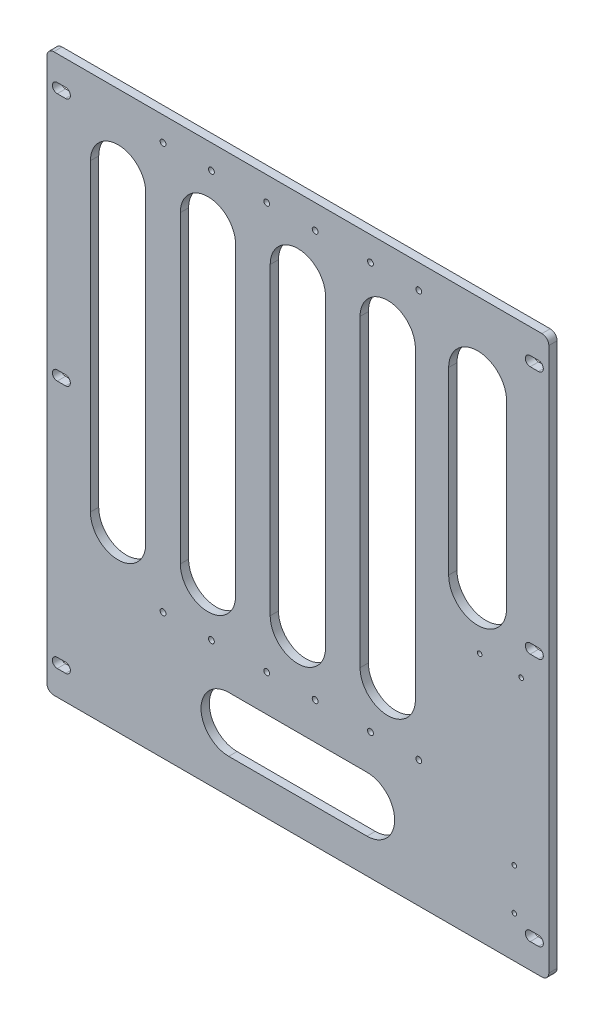
SolidWorks part; units mm, degrees
material "A-玻璃纤维"
ref_plane "前视基准面" through (0, 0, 0) normal (0, 0, 1) x (1, 0, 0)
ref_plane "上视基准面" through (0, 0, 0) normal (0, 1, 0) x (1, 0, 0)
ref_plane "右视基准面" through (0, 0, 0) normal (1, 0, 0) x (0, 0, -1)
sketch "草图1" plane through (0, 0, 0) normal (0, 0, 1) x (1, 0, 0)
  line L1 (-181.5, 201.5) -> (181.5, 201.5)
  line L2 (-181.5, 201.5) -> (-181.5, -201.5)
  line L3 (-181.5, -201.5) -> (181.5, -201.5)
  line L4 (181.5, 201.5) -> (181.5, -201.5)
  line L5 (-181.5, 201.5) -> (181.5, -201.5) construction
  line L6 (-181.5, -201.5) -> (181.5, 201.5) construction
  point P0 (0, 0)
  dimension "D1" = 363
  dimension "D2" = 403
extrude "凸台-拉伸1" add sketch "草图1" along normal blind 6
fillet "圆角1" radius 5 4 edges at (-181.5, 201.5, 3) (181.5, 201.5, 3) (181.5, -201.5, 3) (-181.5, -201.5, 3)
sketch "草图3" plane through (0, 0, 6) normal (0, 0, 1) x (1, 0, 0)
  line L0 (0, 0) -> (-324.6657, 0) construction
  line L2 (0, 0) -> (0, 277.8571) construction
  line L4 (-181.5, 196.5) -> (-181.5, -196.5) construction
  circle A0 centre (-171, -180) radius 3.5
  circle A1 centre (-171, 180) radius 3.5
  circle A3 centre (-171, 0) radius 3.5
  circle A4 centre (171, 0) radius 3.5
  circle A5 centre (171, 180) radius 3.5
  circle A6 centre (171, -180) radius 3.5
  point P0 (-171, -180)
  dimension "D4" = 7
  dimension "D3" = 7
  dimension "D6" = 7
  dimension "D1" = 10.5
  dimension "D2" = 180
  dimension "D8" = 180
extrude "切除-拉伸2" cut sketch "草图3" against normal blind 10
hole_wizard "M5 螺纹孔1" positions "草图4" profile "草图5" tap size "M5" standard "GB"
sketch "草图4" plane through (0, 0, 6) normal (0, 0, 1) x (1, 0, 0)
  line L0 (0, 0) -> (-232.1316, 0) construction
  line L2 (-181.5, 196.5) -> (-181.5, -196.5) construction
  line L4 (0, 0) -> (0, 259.9529) construction
  point P0 (-97.5, -110)
  point P2 (-62.5, -110)
  point P40 (-97.5, 184)
  point P42 (-62.5, 184)
  point P52 (-22.5, -110)
  point P53 (12.5, -110)
  point P54 (-22.5, 184)
  point P55 (12.5, 184)
  point P56 (52.5, -110)
  point P57 (87.5, -110)
  point P58 (52.5, 184)
  point P59 (87.5, 184)
  point P72 (162.5, 184) [skipped]
  point P73 (127.5, 184) [skipped]
  point P74 (162.5, -110) [skipped]
  point P75 (127.5, -110) [skipped]
  dimension "D1" = 110
  dimension "D2" = 4
  dimension "D3" = 84
  dimension "D4" = 35
  dimension "D5" = 84
  dimension "D6" = 35
  dimension "D7" = 294
sketch "草图5" plane through (-97.5, -110, 6) normal (1, 0, 0) x (0, -1, 0)
  line L0 (0, 0) -> (0, 13.6618)
  line L1 (0, 13.6618) -> (2.1, 12.4)
  line L2 (2.1, 12.4) -> (2.1, 0)
  line L5 (2.1, 0) -> (0, 0)
  line L10 (0, 13.6618) -> (-2.1, 12.4) construction
  line L11 (0, -6.35) -> (0, 107.95) construction
  dimension "螺纹孔钻头直径" = 4.2
  dimension "螺纹孔钻头深度" = 12.4
  dimension "导头角度" = 118
cosmetic thread "孔螺蚊线3" parameters "D1"=6, "D2"=5
cosmetic thread "孔螺蚊线4" parameters "D1"=6, "D2"=5
cosmetic thread "孔螺蚊线7" parameters "D1"=6, "D2"=5
cosmetic thread "孔螺蚊线8" parameters "D1"=6, "D2"=5
cosmetic thread "孔螺蚊线9" parameters "D1"=6, "D2"=5
cosmetic thread "孔螺蚊线10" parameters "D1"=6, "D2"=5
cosmetic thread "孔螺蚊线11" parameters "D1"=6, "D2"=5
cosmetic thread "孔螺蚊线12" parameters "D1"=6, "D2"=5
cosmetic thread "孔螺蚊线13" parameters "D1"=6, "D2"=5
cosmetic thread "孔螺蚊线14" parameters "D1"=6, "D2"=5
cosmetic thread "孔螺蚊线15" parameters "D1"=6, "D2"=5
cosmetic thread "孔螺蚊线16" parameters "D1"=6, "D2"=5
sketch "草图6" plane through (0, 0, 6) normal (0, 0, 1) x (1, 0, 0)
  line L0 (-174, 180) -> (-168, 180) construction
  line L1 (-174, 183.5) -> (-168, 183.5)
  line L2 (-174, 176.5) -> (-168, 176.5)
  line L3 (168, 180) -> (174, 180) construction
  line L4 (168, 183.5) -> (174, 183.5)
  line L5 (168, 176.5) -> (174, 176.5)
  line L6 (168, 0) -> (174, 0) construction
  line L7 (168, 3.5) -> (174, 3.5)
  line L8 (168, -3.5) -> (174, -3.5)
  line L9 (168, -180) -> (174, -180) construction
  line L10 (168, -176.5) -> (174, -176.5)
  line L11 (168, -183.5) -> (174, -183.5)
  line L12 (-174, 0) -> (-168, 0) construction
  line L13 (-174, 3.5) -> (-168, 3.5)
  line L14 (-174, -3.5) -> (-168, -3.5)
  line L15 (-174, -180) -> (-168, -180) construction
  line L16 (-174, -176.5) -> (-168, -176.5)
  line L17 (-174, -183.5) -> (-168, -183.5)
  arc A0 (-174, 183.5) -> (-174, 176.5) centre (-174, 180) ccw
  arc A1 (-168, 176.5) -> (-168, 183.5) centre (-168, 180) ccw
  arc A2 (168, 183.5) -> (168, 176.5) centre (168, 180) ccw
  arc A3 (174, 176.5) -> (174, 183.5) centre (174, 180) ccw
  arc A4 (168, 3.5) -> (168, -3.5) centre (168, 0) ccw
  arc A5 (174, -3.5) -> (174, 3.5) centre (174, 0) ccw
  arc A6 (168, -176.5) -> (168, -183.5) centre (168, -180) ccw
  arc A7 (174, -183.5) -> (174, -176.5) centre (174, -180) ccw
  arc A8 (-174, 3.5) -> (-174, -3.5) centre (-174, 0) ccw
  arc A9 (-168, -3.5) -> (-168, 3.5) centre (-168, 0) ccw
  arc A10 (-174, -176.5) -> (-174, -183.5) centre (-174, -180) ccw
  arc A11 (-168, -183.5) -> (-168, -176.5) centre (-168, -180) ccw
  point P2 (-171, 180)
  point P13 (171, 180)
  point P20 (171, 0)
  point P27 (171, -180)
  point P34 (-171, 0)
  point P41 (-171, -180)
  dimension "D1" = 3.5
  dimension "D2" = 6
  dimension "D3" = 3
extrude "切除-拉伸3" cut sketch "草图6" against normal blind 10
sketch "草图7" plane through (0, 0, 6) normal (0, 0, 1) x (1, 0, 0)
  line L0 (0, 0) -> (0, -242.9538) construction
  line L1 (-176.5, -201.5) -> (176.5, -201.5) construction
  line L9 (-50, -156.5) -> (50, -156.5) construction
  line L10 (-50, -136.5) -> (50, -136.5)
  line L11 (-50, -176.5) -> (50, -176.5)
  arc A4 (-50, -136.5) -> (-50, -176.5) centre (-50, -156.5) ccw
  arc A5 (50, -176.5) -> (50, -136.5) centre (50, -156.5) ccw
  point P25 (0, -156.5)
  dimension "D6" = 20
  dimension "D1" = 45
  dimension "D5" = 100
extrude "切除-拉伸4" cut sketch "草图7" against normal blind 10
sketch "草图8" plane through (0, 0, 6) normal (0, 0, 1) x (1, 0, 0)
  line L0 (0, 0) -> (0, 274.3481) construction
  line L1 (0, 0) -> (268.4269, 0) construction
  line L2 (0, 146.5) -> (0, -73.5) construction
  line L3 (20, 146.5) -> (20, -73.5)
  line L4 (-20, 146.5) -> (-20, -73.5)
  line L5 (176.5, 201.5) -> (-176.5, 201.5) construction
  line L6 (65, 146.5) -> (65, -73.5) construction
  line L7 (85, 146.5) -> (85, -73.5)
  line L8 (45, 146.5) -> (45, -73.5)
  line L9 (130, 146.5) -> (130, 16.5) construction
  line L12 (-130, 146.5) -> (-130, -73.5) construction
  line L13 (-150, 146.5) -> (-150, -73.5)
  line L14 (-110, 146.5) -> (-110, -73.5)
  line L15 (-65, 146.5) -> (-65, -73.5) construction
  line L16 (-85, 146.5) -> (-85, -73.5)
  line L17 (-45, 146.5) -> (-45, -73.5)
  line L18 (0, 0) -> (0, -232.9351) construction
  line L22 (150.953, 146.5) -> (150.953, 16.5)
  line L23 (109.047, 146.5) -> (109.047, 16.5)
  line L24 (130, 146.5) -> (130, -73.5) construction
  line L25 (150, 146.5) -> (150, -73.5)
  line L26 (110, 146.5) -> (110, -73.5)
  line L27 (130, 146.5) -> (130, -73.5) construction
  line L28 (150, 146.5) -> (150, -73.5)
  line L29 (110, 146.5) -> (110, -73.5)
  arc A0 (20, 146.5) -> (-20, 146.5) centre (0, 146.5) ccw
  arc A1 (-20, -73.5) -> (20, -73.5) centre (0, -73.5) ccw
  arc A2 (85, 146.5) -> (45, 146.5) centre (65, 146.5) ccw
  arc A3 (45, -73.5) -> (85, -73.5) centre (65, -73.5) ccw
  arc A6 (-150, 146.5) -> (-110, 146.5) centre (-130, 146.5) cw
  arc A7 (-110, -73.5) -> (-150, -73.5) centre (-130, -73.5) cw
  arc A8 (-85, 146.5) -> (-45, 146.5) centre (-65, 146.5) cw
  arc A9 (-45, -73.5) -> (-85, -73.5) centre (-65, -73.5) cw
  arc A12 (150.953, 146.5) -> (109.047, 146.5) centre (130, 146.5) ccw
  arc A13 (109.047, 16.5) -> (150.953, 16.5) centre (130, 16.5) ccw
  arc A16 (150, 146.5) -> (110, 146.5) centre (130, 146.5) ccw
  arc A17 (110, -73.5) -> (150, -73.5) centre (130, -73.5) ccw
  point P6 (0, 36.5)
  point P16 (65, 36.5)
  point P23 (130, 81.5)
  point P29 (-130, 36.5)
  point P36 (-65, 36.5)
  point P44 (130, 36.5)
  point P53 (130, 36.5)
  point P60 (130, 36.5)
  dimension "D3" = 20
  dimension "D7" = 130
  dimension "D1" = 55
  dimension "D2" = 220
  dimension "D5" = 65
  dimension "D6" = 55
  dimension "D4" = 3
extrude "切除-拉伸5" cut sketch "草图8" against normal blind 10
hole_wizard "M4 螺纹孔1" positions "草图9" profile "草图10" tap size "M4" standard "GB"
sketch "草图9" plane through (0, 0, 6) normal (0, 0, 1) x (1, 0, 0)
  line L0 (-176.5, -201.5) -> (176.5, -201.5) construction
  line L1 (181.5, -196.5) -> (181.5, 196.5) construction
  point P0 (156.5, -171.5)
  point P3 (156.5, -141.5)
  point P12 (161.5, -21.5)
  point P15 (131.5, -21.5)
  dimension "D1" = 30
  dimension "D2" = 30
  dimension "D3" = 25
  dimension "D4" = 20
  dimension "D5" = 180
  dimension "D6" = 30
sketch "草图10" plane through (156.5, -171.5, 6) normal (1, 0, 0) x (0, -1, 0)
  line L0 (0, 0) -> (0, 11.0914)
  line L1 (0, 11.0914) -> (1.65, 10.1)
  line L2 (1.65, 10.1) -> (1.65, 0)
  line L5 (1.65, 0) -> (0, 0)
  line L10 (0, 11.0914) -> (-1.65, 10.1) construction
  line L11 (0, -6.35) -> (0, 107.95) construction
  dimension "螺纹孔钻头直径" = 3.3
  dimension "螺纹孔钻头深度" = 10.1
  dimension "导头角度" = 118
cosmetic thread "孔螺蚊线17" parameters "D1"=6, "D2"=4
cosmetic thread "孔螺蚊线18" parameters "D1"=6, "D2"=4
cosmetic thread "孔螺蚊线19" parameters "D1"=6, "D2"=4
cosmetic thread "孔螺蚊线20" parameters "D1"=6, "D2"=4
sketch "折弯-线1" plane through (0, 0, 0) normal (0, 1, 0) x (1, 0, 0)
sketch "边界框1" plane through (0, 0, 0) normal (0, 1, 0) x (1, 0, 0)
